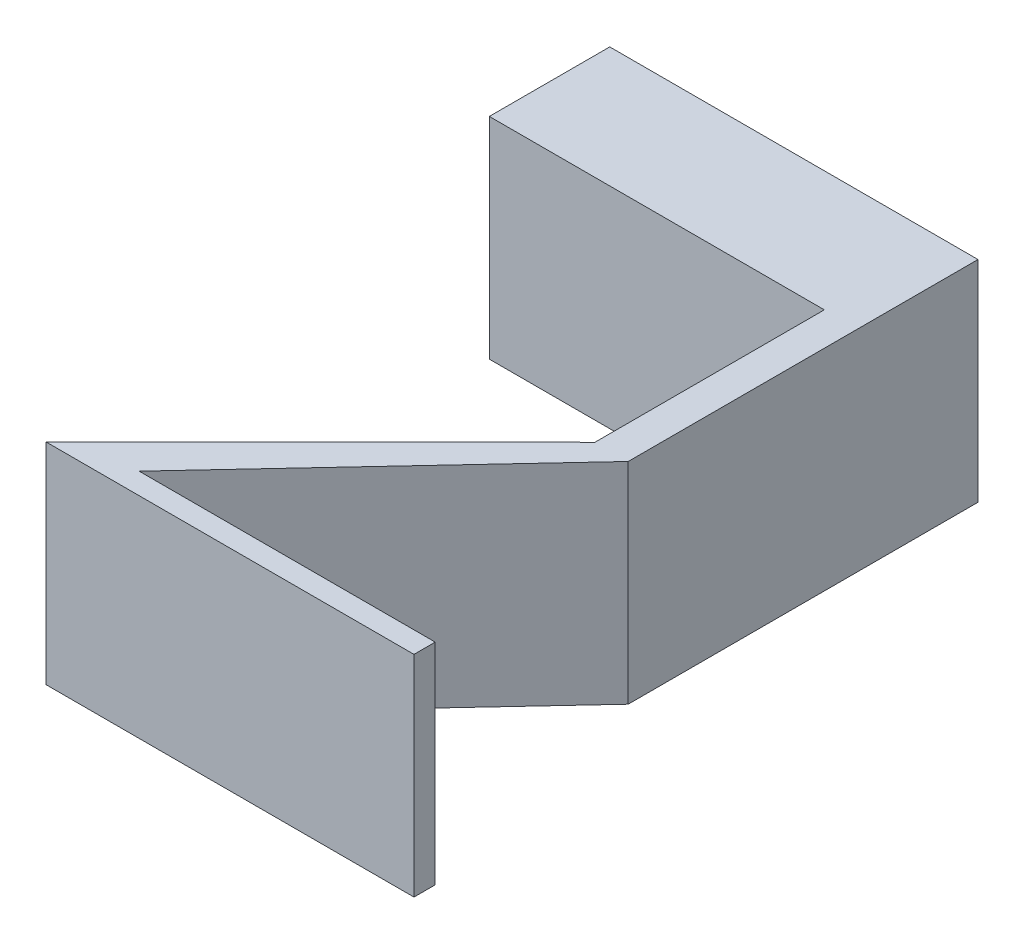
SolidWorks part; units mm, degrees
ref_plane "Front Plane" through (0, 0, 0) normal (0, 0, 1) x (1, 0, 0)
ref_plane "Top Plane" through (0, 0, 0) normal (0, 1, 0) x (1, 0, 0)
ref_plane "Right Plane" through (0, 0, 0) normal (1, 0, 0) x (0, 0, -1)
sketch "Sketch1" plane through (0, 0, 0) normal (0, 0, 1) x (1, 0, 0)
  line L1 (-69.7289, -49.5143) -> (69.7289, -49.5143)
  line L2 (-69.7289, -49.5143) -> (-69.7289, 49.5143)
  line L3 (-69.7289, 49.5143) -> (69.7289, 49.5143)
  line L4 (69.7289, -49.5143) -> (69.7289, 49.5143)
  line L5 (-69.7289, -49.5143) -> (69.7289, 49.5143) construction
  line L6 (-69.7289, 49.5143) -> (69.7289, -49.5143) construction
  point P0 (0, 0)
extrude "Boss-Extrude1" add sketch "Sketch1" along normal blind 10
sketch "Sketch2" plane through (0, 49.5143, 0) normal (0, 1, 0) x (1, 0, 0)
  line L0 (-69.7289, 0) -> (41.4912, 119.1467)
  line L1 (41.4912, 119.1467) -> (25.8299, 119.1467)
  line L2 (25.8299, 119.1467) -> (-103.6092, -10)
  line L3 (-103.6092, -10) -> (-69.7289, -10)
  line L4 (-69.7289, -10) -> (-69.7289, 0)
extrude "Boss-Extrude2" add sketch "Sketch2" against normal up to surface (99.0286 mm away) up to face at (0, -49.5143, 5)
sketch "Sketch3" plane through (0, 49.5143, 0) normal (0, 1, 0) x (1, 0, 0)
  line L0 (41.4912, 119.1467) -> (41.4912, 283.9149)
  line L1 (41.4912, 283.9149) -> (-131.9762, 283.9149)
  line L2 (-131.9762, 283.9149) -> (-131.9762, 227.1945)
  line L3 (-131.9762, 227.1945) -> (25.8299, 227.1945)
  line L4 (25.8299, 227.1945) -> (25.8299, 119.1467)
  line L5 (25.8299, 119.1467) -> (41.4912, 119.1467)
extrude "Boss-Extrude3" add sketch "Sketch3" against normal up to surface (99.0286 mm away) contours L3 L4 L5 L0 L1 L2 up to face at (5.5735, -49.5143, -36.3822)
